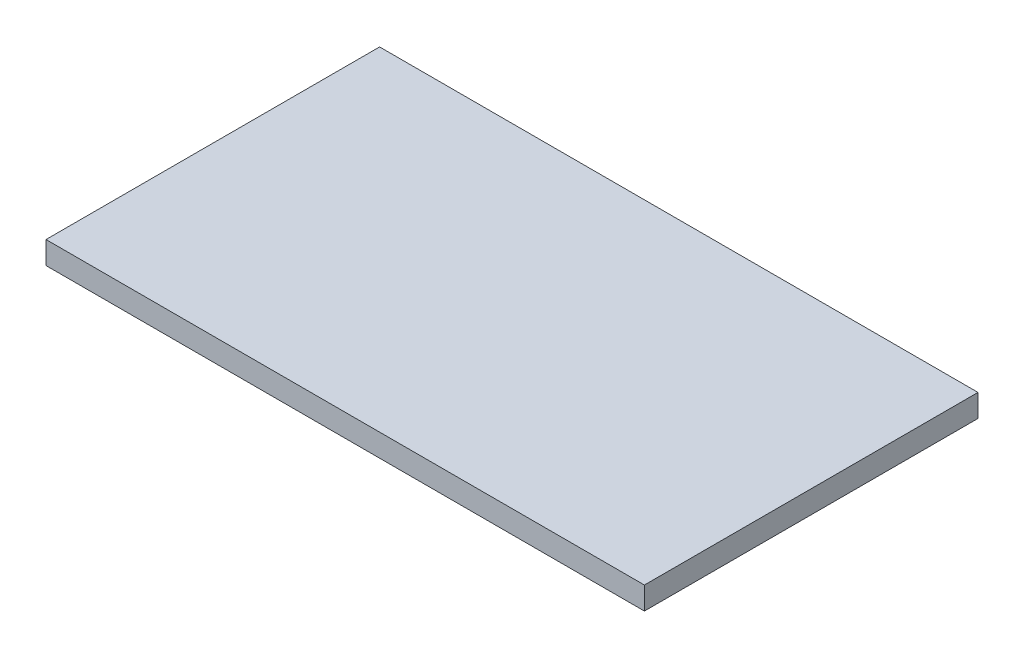
SolidWorks part; units mm, degrees
ref_plane "Front Plane" through (0, 0, 0) normal (0, 0, 1) x (1, 0, 0)
ref_plane "Top Plane" through (0, 0, 0) normal (0, 1, 0) x (1, 0, 0)
ref_plane "Right Plane" through (0, 0, 0) normal (1, 0, 0) x (0, 0, -1)
sketch "Sketch1" plane through (0, 0, 0) normal (0, 1, 0) x (1, 0, 0)
  line L1 (-74.041, -41.275) -> (74.041, -41.275)
  line L2 (-74.041, -41.275) -> (-74.041, 41.275)
  line L3 (-74.041, 41.275) -> (74.041, 41.275)
  line L4 (74.041, -41.275) -> (74.041, 41.275)
  line L5 (-74.041, -41.275) -> (74.041, 41.275) construction
  line L6 (-74.041, 41.275) -> (74.041, -41.275) construction
  point P0 (0, 0)
  dimension "D1" = 148.082
  dimension "D2" = 82.55
extrude "Boss-Extrude1" add sketch "Sketch1" along normal blind 5.588
